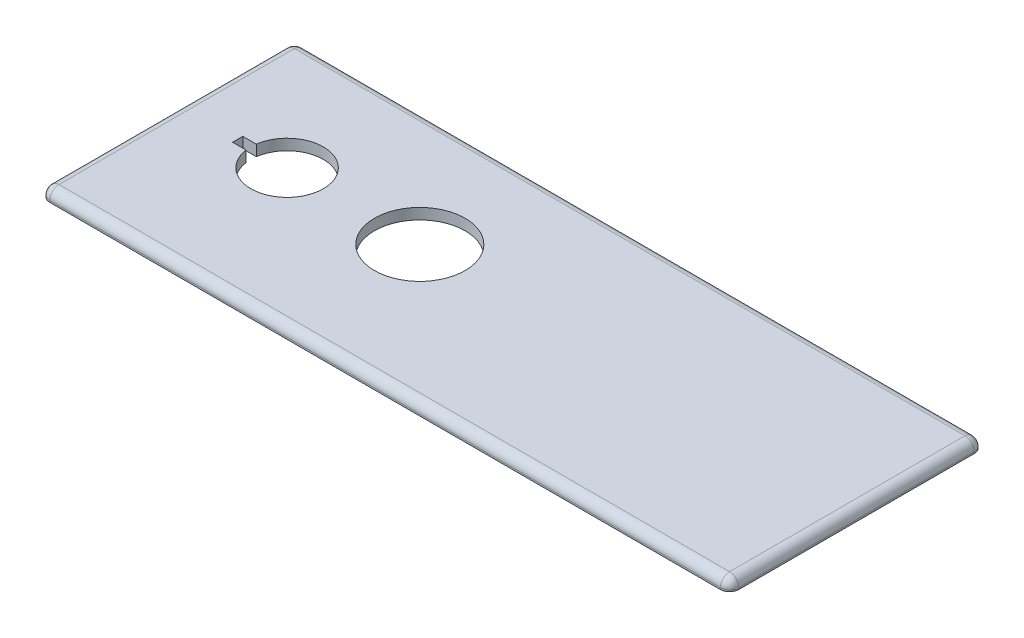
SolidWorks part; units mm, degrees
ref_plane "Front Plane" through (0, 0, 0) normal (0, 0, 1) x (1, 0, 0)
ref_plane "Top Plane" through (0, 0, 0) normal (0, 1, 0) x (1, 0, 0)
ref_plane "Right Plane" through (0, 0, 0) normal (1, 0, 0) x (0, 0, -1)
sketch "Sketch1" plane through (0, 0, 0) normal (0, 1, 0) x (1, 0, 0)
  line L1 (-95, -35) -> (95, -35)
  line L2 (-95, -35) -> (-95, 35)
  line L3 (-95, 35) -> (95, 35)
  line L4 (95, -35) -> (95, 35)
  line L5 (-95, -35) -> (95, 35) construction
  line L6 (-95, 35) -> (95, -35) construction
  point P0 (0, 0)
  dimension "D1" = 190
  dimension "D2" = 70
extrude "Boss-Extrude1" add sketch "Sketch1" along normal blind 3
fillet "Fillet6" radius 2.54 4 edges at (95, 1.5, -35) (95, 1.5, 35) (-95, 1.5, 35) (-95, 1.5, -35)
fillet "Fillet7" radius 2.54 8 edges at (94.2561, 3, 34.2561) (-94.2561, 3, 34.2561) (-94.2561, 3, -34.2561) (94.2561, 3, -34.2561) (-95, 3, 0) (0, 3, 35) (0, 3, -35) (95, 3, 0)
sketch "Sketch2" plane through (0, 3, 0) normal (0, 1, 0) x (1, 0, 0)
  line L0 (-95, -32.46) -> (-95, 32.46) construction
  line L2 (-78.6278, 1.5804) -> (-71.3722, 1.5804)
  line L3 (-78.6278, 1.5804) -> (-78.6278, 4.3839)
  line L4 (-78.6278, 4.3839) -> (-71.3722, 4.3839)
  line L5 (-71.3722, 1.5804) -> (-71.3722, 4.3839)
  line L6 (-78.6278, 1.5804) -> (-71.3722, 4.3839) construction
  line L7 (-78.6278, 4.3839) -> (-71.3722, 1.5804) construction
  circle A0 centre (-65, 2.9822) radius 10
  circle A1 centre (-28.4154, 2.9822) radius 12.5
  point P6 (-75, 2.9822)
  dimension "D3" = 25
  dimension "D4" = 20
  dimension "D1" = 30
  dimension "D2" = 36.5846
extrude "Cut-Extrude1" cut sketch "Sketch2" against normal blind 6.5782 contours L2 A0 L4 L5 | A1 | A0 L4 L3 L2 | L4 A0 L2 L5
